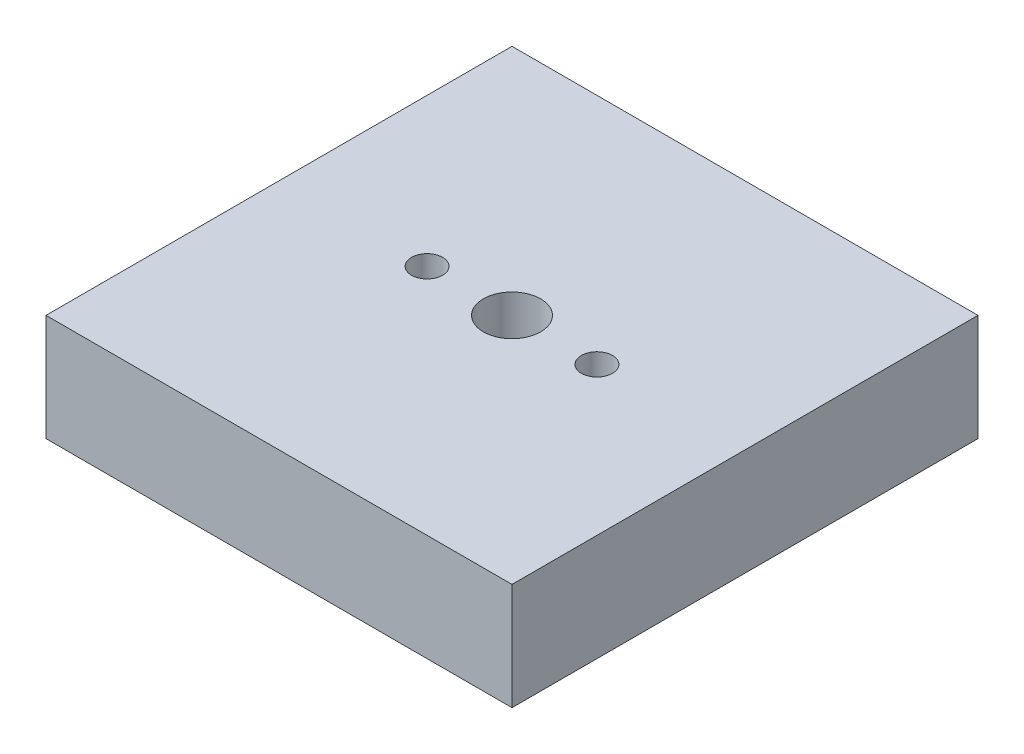
SolidWorks part; units mm, degrees
ref_plane "Front Plane" through (0, 0, 0) normal (0, 0, 1) x (1, 0, 0)
ref_plane "Top Plane" through (0, 0, 0) normal (0, 1, 0) x (1, 0, 0)
ref_plane "Right Plane" through (0, 0, 0) normal (1, 0, 0) x (0, 0, -1)
sketch "Sketch1" plane through (0, 0, 0) normal (0, 1, 0) x (1, 0, 0)
  line L0 (0, 4.8) -> (9.6, 4.8) construction
  line L1 (0, 0) -> (9.6, 0)
  line L2 (0, 0) -> (0, 9.6)
  line L3 (0, 9.6) -> (9.6, 9.6)
  line L4 (9.6, 0) -> (9.6, 9.6)
  line L5 (4.8, 4.8) -> (3.05, 4.8) construction
  line L6 (4.8, 4.8) -> (6.55, 4.8) construction
  circle A0 centre (4.8, 4.8) radius 0.59
  circle A1 centre (3.05, 4.8) radius 0.32
  circle A2 centre (6.55, 4.8) radius 0.32
extrude "Boss-Extrude1" add sketch "Sketch1" along normal blind 2.2
